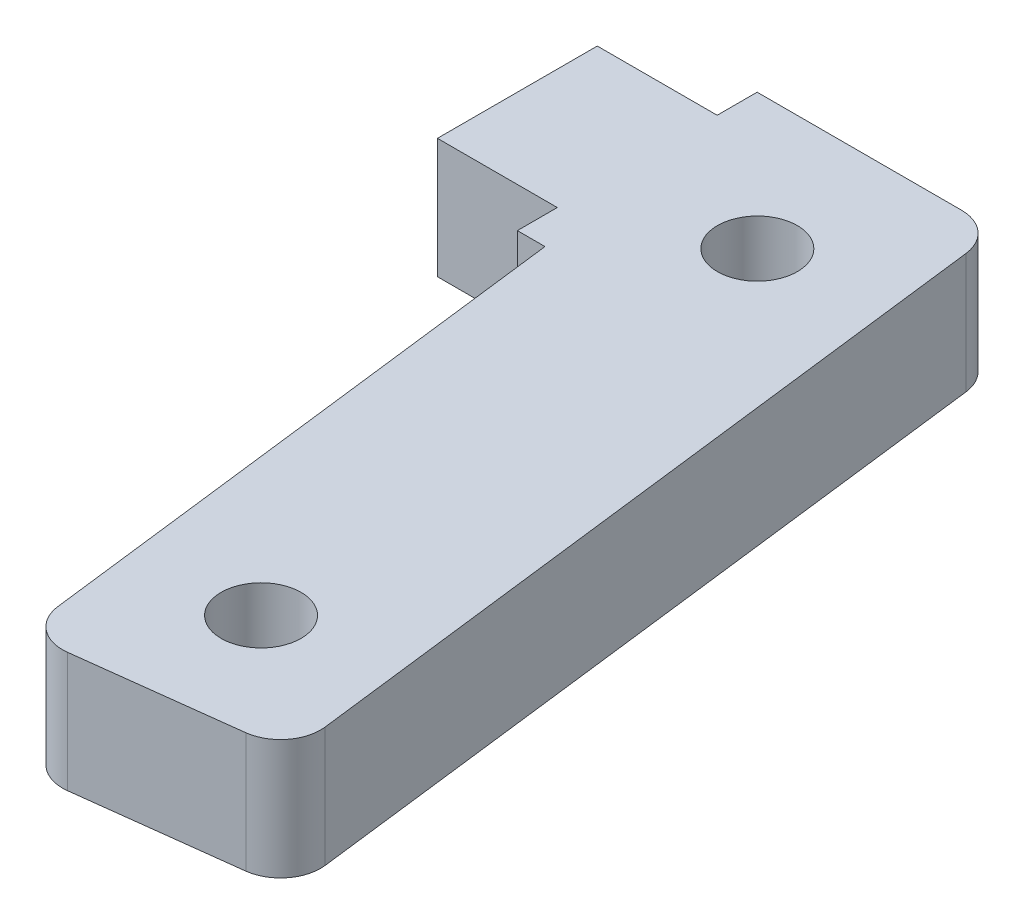
SolidWorks part; units mm, degrees
ref_plane "Front Plane" through (0, 0, 0) normal (0, 0, 1) x (1, 0, 0)
ref_plane "Top Plane" through (0, 0, 0) normal (0, 1, 0) x (1, 0, 0)
ref_plane "Right Plane" through (0, 0, 0) normal (1, 0, 0) x (0, 0, -1)
sketch "Sketch2" plane through (0, 0, 0) normal (0, 1, 0) x (1, 0, 0)
  line L3 (20.7482, 19.9333) -> (14.7482, 19.9333)
  line L4 (14.7482, 13.9333) -> (15.4399, 13.9333)
  line L5 (15.4399, 13.9333) -> (17.2679, -0.9549)
  line L6 (17.2679, -0.9549) -> (23.2232, -0.2236)
  line L7 (23.2232, -0.2236) -> (20.7482, 19.9333)
  line L8 (14.7482, 18.9333) -> (11.7482, 18.9333)
  line L9 (11.7482, 18.9333) -> (11.7482, 14.9333)
  line L10 (11.7482, 14.9333) -> (14.7482, 14.9333)
  line L12 (14.7482, 19.9333) -> (14.7482, 18.9333)
  line L13 (14.7482, 14.9333) -> (14.7482, 13.9333)
  line L14 (11.7482, 16.9333) -> (21.1868, 16.3618) construction
  line L15 (20.2456, -0.5892) -> (18.1416, 16.5462) construction
  circle A0 centre (18.1416, 16.5462) radius 1
  circle A1 centre (19.88, 2.3884) radius 1
  dimension "D6" = 2
  dimension "D7" = 2
  dimension "D8" = 3
  dimension "D1" = 97
  dimension "D2" = 15
  dimension "D3" = 6
  dimension "D4" = 6
  dimension "D5" = 6
extrude "Boss-Extrude1" add sketch "Sketch2" along normal blind 3
fillet "Fillet1" radius 1 3 edges at (17.2679, 1.5, 0.9549) (23.2232, 1.5, 0.2236) (20.7482, 1.5, -19.9333)
